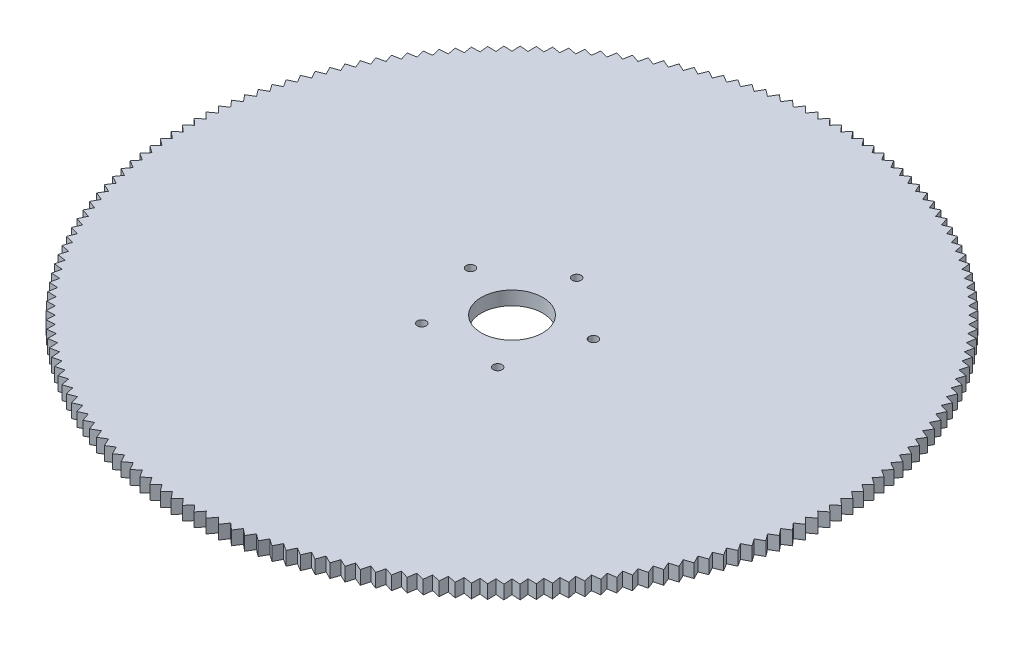
SolidWorks part; units mm, degrees
ref_plane "Front Plane" through (0, 0, 0) normal (0, 0, 1) x (1, 0, 0)
ref_plane "Top Plane" through (0, 0, 0) normal (0, 1, 0) x (1, 0, 0)
ref_plane "Right Plane" through (0, 0, 0) normal (1, 0, 0) x (0, 0, -1)
sketch "Sketch1" plane through (0, 0, 0) normal (0, 1, 0) x (1, 0, 0)
  line L0 (5.3396, 152.9068) -> (2.6179, 149.9772)
  line L1 (5.3396, 152.9068) -> (7.8504, 149.7944)
  line L2 (0, 153) -> (-2.6179, 149.9772)
  line L3 (10.6727, 152.6273) -> (7.8504, 149.7944)
  line L4 (0, 153) -> (2.6179, 149.9772)
  line L5 (10.6727, 152.6273) -> (13.0734, 149.4292)
  line L6 (15.9929, 152.1618) -> (13.0734, 149.4292)
  line L7 (15.9929, 152.1618) -> (18.2804, 148.8819)
  line L8 (21.2935, 151.511) -> (18.2804, 148.8819)
  line L9 (21.2935, 151.511) -> (23.4652, 148.1533)
  line L10 (26.5682, 150.6756) -> (23.4652, 148.1533)
  line L11 (26.5682, 150.6756) -> (28.6213, 147.2441)
  line L12 (31.8105, 149.6566) -> (28.6213, 147.2441)
  line L13 (31.8105, 149.6566) -> (33.7427, 146.1555)
  line L14 (37.0141, 148.4552) -> (33.7427, 146.1555)
  line L15 (37.0141, 148.4552) -> (38.8229, 144.8889)
  line L16 (42.1725, 147.073) -> (38.8229, 144.8889)
  line L17 (42.1725, 147.073) -> (43.8558, 143.4457)
  line L18 (47.2796, 145.5116) -> (43.8558, 143.4457)
  line L19 (47.2796, 145.5116) -> (48.8352, 141.8278)
  line L20 (52.3291, 143.773) -> (48.8352, 141.8278)
  line L21 (52.3291, 143.773) -> (53.7552, 140.0371)
  line L22 (57.3148, 141.8591) -> (53.7552, 140.0371)
  line L23 (57.3148, 141.8591) -> (58.6097, 138.0757)
  line L24 (62.2307, 139.7725) -> (58.6097, 138.0757)
  line L25 (62.2307, 139.7725) -> (63.3927, 135.9462)
  line L26 (67.0708, 137.5155) -> (63.3927, 135.9462)
  line L27 (67.0708, 137.5155) -> (68.0986, 133.651)
  line L28 (71.8291, 135.091) -> (68.0986, 133.651)
  line L29 (71.8291, 135.091) -> (72.7214, 131.193)
  line L30 (76.5, 132.5019) -> (72.7214, 131.193)
  line L31 (76.5, 132.5019) -> (77.2557, 128.5751)
  line L32 (81.0776, 129.7514) -> (77.2557, 128.5751)
  line L33 (81.0776, 129.7514) -> (81.6959, 125.8006)
  line L34 (85.5565, 126.8427) -> (81.6959, 125.8006)
  line L35 (85.5565, 126.8427) -> (86.0365, 122.8728)
  line L36 (89.9311, 123.7796) -> (86.0365, 122.8728)
  line L37 (89.9311, 123.7796) -> (90.2723, 119.7953)
  line L38 (94.1962, 120.5656) -> (90.2723, 119.7953)
  line L39 (94.1962, 120.5656) -> (94.3981, 116.5719)
  line L40 (98.3465, 117.2048) -> (94.3981, 116.5719)
  line L41 (98.3465, 117.2048) -> (98.4089, 113.2064)
  line L42 (102.377, 113.7012) -> (98.4089, 113.2064)
  line L43 (102.377, 113.7012) -> (102.2998, 109.7031)
  line L44 (106.2827, 110.059) -> (102.2998, 109.7031)
  line L45 (106.2827, 110.059) -> (106.066, 106.066)
  line L46 (110.059, 106.2827) -> (106.066, 106.066)
  line L47 (110.059, 106.2827) -> (109.7031, 102.2998)
  line L48 (113.7012, 102.377) -> (109.7031, 102.2998)
  line L49 (113.7012, 102.377) -> (113.2064, 98.4089)
  line L50 (117.2048, 98.3465) -> (113.2064, 98.4089)
  line L51 (117.2048, 98.3465) -> (116.5719, 94.3981)
  line L52 (120.5656, 94.1962) -> (116.5719, 94.3981)
  line L53 (120.5656, 94.1962) -> (119.7953, 90.2723)
  line L54 (123.7796, 89.9311) -> (119.7953, 90.2723)
  line L55 (123.7796, 89.9311) -> (122.8728, 86.0365)
  line L56 (126.8427, 85.5565) -> (122.8728, 86.0365)
  line L57 (126.8427, 85.5565) -> (125.8006, 81.6959)
  line L58 (129.7514, 81.0776) -> (125.8006, 81.6959)
  line L59 (129.7514, 81.0776) -> (128.5751, 77.2557)
  line L60 (132.5019, 76.5) -> (128.5751, 77.2557)
  line L61 (132.5019, 76.5) -> (131.193, 72.7214)
  line L62 (135.091, 71.8291) -> (131.193, 72.7214)
  line L63 (135.091, 71.8291) -> (133.651, 68.0986)
  line L64 (137.5155, 67.0708) -> (133.651, 68.0986)
  line L65 (137.5155, 67.0708) -> (135.9462, 63.3927)
  line L66 (139.7725, 62.2307) -> (135.9462, 63.3927)
  line L67 (139.7725, 62.2307) -> (138.0757, 58.6097)
  line L68 (141.8591, 57.3148) -> (138.0757, 58.6097)
  line L69 (141.8591, 57.3148) -> (140.0371, 53.7552)
  line L70 (143.773, 52.3291) -> (140.0371, 53.7552)
  line L71 (143.773, 52.3291) -> (141.8278, 48.8352)
  line L72 (145.5116, 47.2796) -> (141.8278, 48.8352)
  line L73 (145.5116, 47.2796) -> (143.4457, 43.8558)
  line L74 (147.073, 42.1725) -> (143.4457, 43.8558)
  line L75 (147.073, 42.1725) -> (144.8889, 38.8229)
  line L76 (148.4552, 37.0141) -> (144.8889, 38.8229)
  line L77 (148.4552, 37.0141) -> (146.1555, 33.7427)
  line L78 (149.6566, 31.8105) -> (146.1555, 33.7427)
  line L79 (149.6566, 31.8105) -> (147.2441, 28.6213)
  line L80 (150.6756, 26.5682) -> (147.2441, 28.6213)
  line L81 (150.6756, 26.5682) -> (148.1533, 23.4652)
  line L82 (151.511, 21.2935) -> (148.1533, 23.4652)
  line L83 (151.511, 21.2935) -> (148.8819, 18.2804)
  line L84 (152.1618, 15.9929) -> (148.8819, 18.2804)
  line L85 (152.1618, 15.9929) -> (149.4292, 13.0734)
  line L86 (152.6273, 10.6727) -> (149.4292, 13.0734)
  line L87 (152.6273, 10.6727) -> (149.7944, 7.8504)
  line L88 (152.9068, 5.3396) -> (149.7944, 7.8504)
  line L89 (152.9068, 5.3396) -> (149.9772, 2.6179)
  line L90 (153, 0) -> (149.9772, 2.6179)
  line L91 (153, 0) -> (149.9772, -2.6179)
  line L92 (152.9068, -5.3396) -> (149.9772, -2.6179)
  line L93 (152.9068, -5.3396) -> (149.7944, -7.8504)
  line L94 (152.6273, -10.6727) -> (149.7944, -7.8504)
  line L95 (152.6273, -10.6727) -> (149.4292, -13.0734)
  line L96 (152.1618, -15.9929) -> (149.4292, -13.0734)
  line L97 (152.1618, -15.9929) -> (148.8819, -18.2804)
  line L98 (151.511, -21.2935) -> (148.8819, -18.2804)
  line L99 (151.511, -21.2935) -> (148.1533, -23.4652)
  line L100 (150.6756, -26.5682) -> (148.1533, -23.4652)
  line L101 (150.6756, -26.5682) -> (147.2441, -28.6213)
  line L102 (149.6566, -31.8105) -> (147.2441, -28.6213)
  line L103 (149.6566, -31.8105) -> (146.1555, -33.7427)
  line L104 (148.4552, -37.0141) -> (146.1555, -33.7427)
  line L105 (148.4552, -37.0141) -> (144.8889, -38.8229)
  line L106 (147.073, -42.1725) -> (144.8889, -38.8229)
  line L107 (147.073, -42.1725) -> (143.4457, -43.8558)
  line L108 (145.5116, -47.2796) -> (143.4457, -43.8558)
  line L109 (145.5116, -47.2796) -> (141.8278, -48.8352)
  line L110 (143.773, -52.3291) -> (141.8278, -48.8352)
  line L111 (143.773, -52.3291) -> (140.0371, -53.7552)
  line L112 (141.8591, -57.3148) -> (140.0371, -53.7552)
  line L113 (141.8591, -57.3148) -> (138.0757, -58.6097)
  line L114 (139.7725, -62.2307) -> (138.0757, -58.6097)
  line L115 (139.7725, -62.2307) -> (135.9462, -63.3927)
  line L116 (137.5155, -67.0708) -> (135.9462, -63.3927)
  line L117 (137.5155, -67.0708) -> (133.651, -68.0986)
  line L118 (135.091, -71.8291) -> (133.651, -68.0986)
  line L119 (135.091, -71.8291) -> (131.193, -72.7214)
  line L120 (132.5019, -76.5) -> (131.193, -72.7214)
  line L121 (132.5019, -76.5) -> (128.5751, -77.2557)
  line L122 (129.7514, -81.0776) -> (128.5751, -77.2557)
  line L123 (129.7514, -81.0776) -> (125.8006, -81.6959)
  line L124 (126.8427, -85.5565) -> (125.8006, -81.6959)
  line L125 (126.8427, -85.5565) -> (122.8728, -86.0365)
  line L126 (123.7796, -89.9311) -> (122.8728, -86.0365)
  line L127 (123.7796, -89.9311) -> (119.7953, -90.2723)
  line L128 (120.5656, -94.1962) -> (119.7953, -90.2723)
  line L129 (120.5656, -94.1962) -> (116.5719, -94.3981)
  line L130 (117.2048, -98.3465) -> (116.5719, -94.3981)
  line L131 (117.2048, -98.3465) -> (113.2064, -98.4089)
  line L132 (113.7012, -102.377) -> (113.2064, -98.4089)
  line L133 (113.7012, -102.377) -> (109.7031, -102.2998)
  line L134 (110.059, -106.2827) -> (109.7031, -102.2998)
  line L135 (110.059, -106.2827) -> (106.066, -106.066)
  line L136 (106.2827, -110.059) -> (106.066, -106.066)
  line L137 (106.2827, -110.059) -> (102.2998, -109.7031)
  line L138 (102.377, -113.7012) -> (102.2998, -109.7031)
  line L139 (102.377, -113.7012) -> (98.4089, -113.2064)
  line L140 (98.3465, -117.2048) -> (98.4089, -113.2064)
  line L141 (98.3465, -117.2048) -> (94.3981, -116.5719)
  line L142 (94.1962, -120.5656) -> (94.3981, -116.5719)
  line L143 (94.1962, -120.5656) -> (90.2723, -119.7953)
  line L144 (89.9311, -123.7796) -> (90.2723, -119.7953)
  line L145 (89.9311, -123.7796) -> (86.0365, -122.8728)
  line L146 (85.5565, -126.8427) -> (86.0365, -122.8728)
  line L147 (85.5565, -126.8427) -> (81.6959, -125.8006)
  line L148 (81.0776, -129.7514) -> (81.6959, -125.8006)
  line L149 (81.0776, -129.7514) -> (77.2557, -128.5751)
  line L150 (76.5, -132.5019) -> (77.2557, -128.5751)
  line L151 (76.5, -132.5019) -> (72.7214, -131.193)
  line L152 (71.8291, -135.091) -> (72.7214, -131.193)
  line L153 (71.8291, -135.091) -> (68.0986, -133.651)
  line L154 (67.0708, -137.5155) -> (68.0986, -133.651)
  line L155 (67.0708, -137.5155) -> (63.3927, -135.9462)
  line L156 (62.2307, -139.7725) -> (63.3927, -135.9462)
  line L157 (62.2307, -139.7725) -> (58.6097, -138.0757)
  line L158 (57.3148, -141.8591) -> (58.6097, -138.0757)
  line L159 (57.3148, -141.8591) -> (53.7552, -140.0371)
  line L160 (52.3291, -143.773) -> (53.7552, -140.0371)
  line L161 (52.3291, -143.773) -> (48.8352, -141.8278)
  line L162 (47.2796, -145.5116) -> (48.8352, -141.8278)
  line L163 (47.2796, -145.5116) -> (43.8558, -143.4457)
  line L164 (42.1725, -147.073) -> (43.8558, -143.4457)
  line L165 (42.1725, -147.073) -> (38.8229, -144.8889)
  line L166 (37.0141, -148.4552) -> (38.8229, -144.8889)
  line L167 (37.0141, -148.4552) -> (33.7427, -146.1555)
  line L168 (31.8105, -149.6566) -> (33.7427, -146.1555)
  line L169 (31.8105, -149.6566) -> (28.6213, -147.2441)
  line L170 (26.5682, -150.6756) -> (28.6213, -147.2441)
  line L171 (26.5682, -150.6756) -> (23.4652, -148.1533)
  line L172 (21.2935, -151.511) -> (23.4652, -148.1533)
  line L173 (21.2935, -151.511) -> (18.2804, -148.8819)
  line L174 (15.9929, -152.1618) -> (18.2804, -148.8819)
  line L175 (15.9929, -152.1618) -> (13.0734, -149.4292)
  line L176 (10.6727, -152.6273) -> (13.0734, -149.4292)
  line L177 (10.6727, -152.6273) -> (7.8504, -149.7944)
  line L178 (5.3396, -152.9068) -> (7.8504, -149.7944)
  line L179 (5.3396, -152.9068) -> (2.6179, -149.9772)
  line L180 (0, -153) -> (2.6179, -149.9772)
  line L181 (0, -153) -> (-2.6179, -149.9772)
  line L182 (-5.3396, -152.9068) -> (-2.6179, -149.9772)
  line L183 (-5.3396, -152.9068) -> (-7.8504, -149.7944)
  line L184 (-10.6727, -152.6273) -> (-7.8504, -149.7944)
  line L185 (-10.6727, -152.6273) -> (-13.0734, -149.4292)
  line L186 (-15.9929, -152.1618) -> (-13.0734, -149.4292)
  line L187 (-15.9929, -152.1618) -> (-18.2804, -148.8819)
  line L188 (-21.2935, -151.511) -> (-18.2804, -148.8819)
  line L189 (-21.2935, -151.511) -> (-23.4652, -148.1533)
  line L190 (-26.5682, -150.6756) -> (-23.4652, -148.1533)
  line L191 (-26.5682, -150.6756) -> (-28.6213, -147.2441)
  line L192 (-31.8105, -149.6566) -> (-28.6213, -147.2441)
  line L193 (-31.8105, -149.6566) -> (-33.7427, -146.1555)
  line L194 (-37.0141, -148.4552) -> (-33.7427, -146.1555)
  line L195 (-37.0141, -148.4552) -> (-38.8229, -144.8889)
  line L196 (-42.1725, -147.073) -> (-38.8229, -144.8889)
  line L197 (-42.1725, -147.073) -> (-43.8558, -143.4457)
  line L198 (-47.2796, -145.5116) -> (-43.8558, -143.4457)
  line L199 (-47.2796, -145.5116) -> (-48.8352, -141.8278)
  line L200 (-52.3291, -143.773) -> (-48.8352, -141.8278)
  line L201 (-52.3291, -143.773) -> (-53.7552, -140.0371)
  line L202 (-57.3148, -141.8591) -> (-53.7552, -140.0371)
  line L203 (-57.3148, -141.8591) -> (-58.6097, -138.0757)
  line L204 (-62.2307, -139.7725) -> (-58.6097, -138.0757)
  line L205 (-62.2307, -139.7725) -> (-63.3927, -135.9462)
  line L206 (-67.0708, -137.5155) -> (-63.3927, -135.9462)
  line L207 (-67.0708, -137.5155) -> (-68.0986, -133.651)
  line L208 (-71.8291, -135.091) -> (-68.0986, -133.651)
  line L209 (-71.8291, -135.091) -> (-72.7214, -131.193)
  line L210 (-76.5, -132.5019) -> (-72.7214, -131.193)
  line L211 (-76.5, -132.5019) -> (-77.2557, -128.5751)
  line L212 (-81.0776, -129.7514) -> (-77.2557, -128.5751)
  line L213 (-81.0776, -129.7514) -> (-81.6959, -125.8006)
  line L214 (-85.5565, -126.8427) -> (-81.6959, -125.8006)
  line L215 (-85.5565, -126.8427) -> (-86.0365, -122.8728)
  line L216 (-89.9311, -123.7796) -> (-86.0365, -122.8728)
  line L217 (-89.9311, -123.7796) -> (-90.2723, -119.7953)
  line L218 (-94.1962, -120.5656) -> (-90.2723, -119.7953)
  line L219 (-94.1962, -120.5656) -> (-94.3981, -116.5719)
  line L220 (-98.3465, -117.2048) -> (-94.3981, -116.5719)
  line L221 (-98.3465, -117.2048) -> (-98.4089, -113.2064)
  line L222 (-102.377, -113.7012) -> (-98.4089, -113.2064)
  line L223 (-102.377, -113.7012) -> (-102.2998, -109.7031)
  line L224 (-106.2827, -110.059) -> (-102.2998, -109.7031)
  line L225 (-106.2827, -110.059) -> (-106.066, -106.066)
  line L226 (-110.059, -106.2827) -> (-106.066, -106.066)
  line L227 (-110.059, -106.2827) -> (-109.7031, -102.2998)
  line L228 (-113.7012, -102.377) -> (-109.7031, -102.2998)
  line L229 (-113.7012, -102.377) -> (-113.2064, -98.4089)
  line L230 (-117.2048, -98.3465) -> (-113.2064, -98.4089)
  line L231 (-117.2048, -98.3465) -> (-116.5719, -94.3981)
  line L232 (-120.5656, -94.1962) -> (-116.5719, -94.3981)
  line L233 (-120.5656, -94.1962) -> (-119.7953, -90.2723)
  line L234 (-123.7796, -89.9311) -> (-119.7953, -90.2723)
  line L235 (-123.7796, -89.9311) -> (-122.8728, -86.0365)
  line L236 (-126.8427, -85.5565) -> (-122.8728, -86.0365)
  line L237 (-126.8427, -85.5565) -> (-125.8006, -81.6959)
  line L238 (-129.7514, -81.0776) -> (-125.8006, -81.6959)
  line L239 (-129.7514, -81.0776) -> (-128.5751, -77.2557)
  line L240 (-132.5019, -76.5) -> (-128.5751, -77.2557)
  line L241 (-132.5019, -76.5) -> (-131.193, -72.7214)
  line L242 (-135.091, -71.8291) -> (-131.193, -72.7214)
  line L243 (-135.091, -71.8291) -> (-133.651, -68.0986)
  line L244 (-137.5155, -67.0708) -> (-133.651, -68.0986)
  line L245 (-137.5155, -67.0708) -> (-135.9462, -63.3927)
  line L246 (-139.7725, -62.2307) -> (-135.9462, -63.3927)
  line L247 (-139.7725, -62.2307) -> (-138.0757, -58.6097)
  line L248 (-141.8591, -57.3148) -> (-138.0757, -58.6097)
  line L249 (-141.8591, -57.3148) -> (-140.0371, -53.7552)
  line L250 (-143.773, -52.3291) -> (-140.0371, -53.7552)
  line L251 (-143.773, -52.3291) -> (-141.8278, -48.8352)
  line L252 (-145.5116, -47.2796) -> (-141.8278, -48.8352)
  line L253 (-145.5116, -47.2796) -> (-143.4457, -43.8558)
  line L254 (-147.073, -42.1725) -> (-143.4457, -43.8558)
  line L255 (-147.073, -42.1725) -> (-144.8889, -38.8229)
  line L256 (-148.4552, -37.0141) -> (-144.8889, -38.8229)
  line L257 (-148.4552, -37.0141) -> (-146.1555, -33.7427)
  line L258 (-149.6566, -31.8105) -> (-146.1555, -33.7427)
  line L259 (-149.6566, -31.8105) -> (-147.2441, -28.6213)
  line L260 (-150.6756, -26.5682) -> (-147.2441, -28.6213)
  line L261 (-150.6756, -26.5682) -> (-148.1533, -23.4652)
  line L262 (-151.511, -21.2935) -> (-148.1533, -23.4652)
  line L263 (-151.511, -21.2935) -> (-148.8819, -18.2804)
  line L264 (-152.1618, -15.9929) -> (-148.8819, -18.2804)
  line L265 (-152.1618, -15.9929) -> (-149.4292, -13.0734)
  line L266 (-152.6273, -10.6727) -> (-149.4292, -13.0734)
  line L267 (-152.6273, -10.6727) -> (-149.7944, -7.8504)
  line L268 (-152.9068, -5.3396) -> (-149.7944, -7.8504)
  line L269 (-152.9068, -5.3396) -> (-149.9772, -2.6179)
  line L270 (-153, 0) -> (-149.9772, -2.6179)
  line L271 (-153, 0) -> (-149.9772, 2.6179)
  line L272 (-152.9068, 5.3396) -> (-149.9772, 2.6179)
  line L273 (-152.9068, 5.3396) -> (-149.7944, 7.8504)
  line L274 (-152.6273, 10.6727) -> (-149.7944, 7.8504)
  line L275 (-152.6273, 10.6727) -> (-149.4292, 13.0734)
  line L276 (-152.1618, 15.9929) -> (-149.4292, 13.0734)
  line L277 (-152.1618, 15.9929) -> (-148.8819, 18.2804)
  line L278 (-151.511, 21.2935) -> (-148.8819, 18.2804)
  line L279 (-151.511, 21.2935) -> (-148.1533, 23.4652)
  line L280 (-150.6756, 26.5682) -> (-148.1533, 23.4652)
  line L281 (-150.6756, 26.5682) -> (-147.2441, 28.6213)
  line L282 (-149.6566, 31.8105) -> (-147.2441, 28.6213)
  line L283 (-149.6566, 31.8105) -> (-146.1555, 33.7427)
  line L284 (-148.4552, 37.0141) -> (-146.1555, 33.7427)
  line L285 (-148.4552, 37.0141) -> (-144.8889, 38.8229)
  line L286 (-147.073, 42.1725) -> (-144.8889, 38.8229)
  line L287 (-147.073, 42.1725) -> (-143.4457, 43.8558)
  line L288 (-145.5116, 47.2796) -> (-143.4457, 43.8558)
  line L289 (-145.5116, 47.2796) -> (-141.8278, 48.8352)
  line L290 (-143.773, 52.3291) -> (-141.8278, 48.8352)
  line L291 (-143.773, 52.3291) -> (-140.0371, 53.7552)
  line L292 (-141.8591, 57.3148) -> (-140.0371, 53.7552)
  line L293 (-141.8591, 57.3148) -> (-138.0757, 58.6097)
  line L294 (-139.7725, 62.2307) -> (-138.0757, 58.6097)
  line L295 (-139.7725, 62.2307) -> (-135.9462, 63.3927)
  line L296 (-137.5155, 67.0708) -> (-135.9462, 63.3927)
  line L297 (-137.5155, 67.0708) -> (-133.651, 68.0986)
  line L298 (-135.091, 71.8291) -> (-133.651, 68.0986)
  line L299 (-135.091, 71.8291) -> (-131.193, 72.7214)
  line L300 (-132.5019, 76.5) -> (-131.193, 72.7214)
  line L301 (-132.5019, 76.5) -> (-128.5751, 77.2557)
  line L302 (-129.7514, 81.0776) -> (-128.5751, 77.2557)
  line L303 (-129.7514, 81.0776) -> (-125.8006, 81.6959)
  line L304 (-126.8427, 85.5565) -> (-125.8006, 81.6959)
  line L305 (-126.8427, 85.5565) -> (-122.8728, 86.0365)
  line L306 (-123.7796, 89.9311) -> (-122.8728, 86.0365)
  line L307 (-123.7796, 89.9311) -> (-119.7953, 90.2723)
  line L308 (-120.5656, 94.1962) -> (-119.7953, 90.2723)
  line L309 (-120.5656, 94.1962) -> (-116.5719, 94.3981)
  line L310 (-117.2048, 98.3465) -> (-116.5719, 94.3981)
  line L311 (-117.2048, 98.3465) -> (-113.2064, 98.4089)
  line L312 (-113.7012, 102.377) -> (-113.2064, 98.4089)
  line L313 (-113.7012, 102.377) -> (-109.7031, 102.2998)
  line L314 (-110.059, 106.2827) -> (-109.7031, 102.2998)
  line L315 (-110.059, 106.2827) -> (-106.066, 106.066)
  line L316 (-106.2827, 110.059) -> (-106.066, 106.066)
  line L317 (-106.2827, 110.059) -> (-102.2998, 109.7031)
  line L318 (-102.377, 113.7012) -> (-102.2998, 109.7031)
  line L319 (-102.377, 113.7012) -> (-98.4089, 113.2064)
  line L320 (-98.3465, 117.2048) -> (-98.4089, 113.2064)
  line L321 (-98.3465, 117.2048) -> (-94.3981, 116.5719)
  line L322 (-94.1962, 120.5656) -> (-94.3981, 116.5719)
  line L323 (-94.1962, 120.5656) -> (-90.2723, 119.7953)
  line L324 (-89.9311, 123.7796) -> (-90.2723, 119.7953)
  line L325 (-89.9311, 123.7796) -> (-86.0365, 122.8728)
  line L326 (-85.5565, 126.8427) -> (-86.0365, 122.8728)
  line L327 (-85.5565, 126.8427) -> (-81.6959, 125.8006)
  line L328 (-81.0776, 129.7514) -> (-81.6959, 125.8006)
  line L329 (-81.0776, 129.7514) -> (-77.2557, 128.5751)
  line L330 (-76.5, 132.5019) -> (-77.2557, 128.5751)
  line L331 (-76.5, 132.5019) -> (-72.7214, 131.193)
  line L332 (-71.8291, 135.091) -> (-72.7214, 131.193)
  line L333 (-71.8291, 135.091) -> (-68.0986, 133.651)
  line L334 (-67.0708, 137.5155) -> (-68.0986, 133.651)
  line L335 (-67.0708, 137.5155) -> (-63.3927, 135.9462)
  line L336 (-62.2307, 139.7725) -> (-63.3927, 135.9462)
  line L337 (-62.2307, 139.7725) -> (-58.6097, 138.0757)
  line L338 (-57.3148, 141.8591) -> (-58.6097, 138.0757)
  line L339 (-57.3148, 141.8591) -> (-53.7552, 140.0371)
  line L340 (-52.3291, 143.773) -> (-53.7552, 140.0371)
  line L341 (-52.3291, 143.773) -> (-48.8352, 141.8278)
  line L342 (-47.2796, 145.5116) -> (-48.8352, 141.8278)
  line L343 (-47.2796, 145.5116) -> (-43.8558, 143.4457)
  line L344 (-42.1725, 147.073) -> (-43.8558, 143.4457)
  line L345 (-42.1725, 147.073) -> (-38.8229, 144.8889)
  line L346 (-37.0141, 148.4552) -> (-38.8229, 144.8889)
  line L347 (-37.0141, 148.4552) -> (-33.7427, 146.1555)
  line L348 (-31.8105, 149.6566) -> (-33.7427, 146.1555)
  line L349 (-31.8105, 149.6566) -> (-28.6213, 147.2441)
  line L350 (-26.5682, 150.6756) -> (-28.6213, 147.2441)
  line L351 (-26.5682, 150.6756) -> (-23.4652, 148.1533)
  line L352 (-21.2935, 151.511) -> (-23.4652, 148.1533)
  line L353 (-21.2935, 151.511) -> (-18.2804, 148.8819)
  line L354 (-15.9929, 152.1618) -> (-18.2804, 148.8819)
  line L355 (-15.9929, 152.1618) -> (-13.0734, 149.4292)
  line L356 (-10.6727, 152.6273) -> (-13.0734, 149.4292)
  line L357 (-10.6727, 152.6273) -> (-7.8504, 149.7944)
  line L358 (-5.3396, 152.9068) -> (-7.8504, 149.7944)
  line L359 (-5.3396, 152.9068) -> (-2.6179, 149.9772)
  circle A1 centre (0, 0) radius 14.27
  circle A2 centre (0, 30) radius 2.05
  circle A3 centre (28.5317, 9.2705) radius 2.05
  circle A4 centre (17.6336, -24.2705) radius 2.05
  circle A5 centre (-17.6336, -24.2705) radius 2.05
  circle A6 centre (-28.5317, 9.2705) radius 2.05
  point P16 (0, 0)
  point P557 (0, 0)
  dimension "D1" = 5
  dimension "D2" = 180
extrude "Boss-Extrude1" add sketch "Sketch1" along normal blind 6.35
